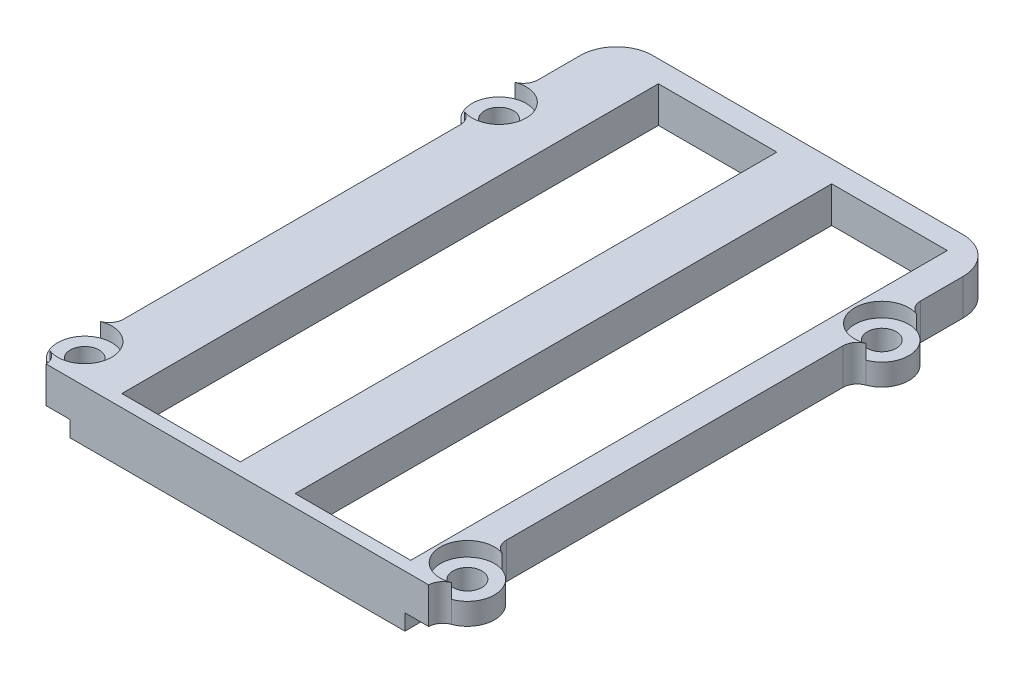
SolidWorks part; units mm, degrees
ref_plane "Front Plane" through (0, 0, 0) normal (0, 0, 1) x (1, 0, 0)
ref_plane "Top Plane" through (0, 0, 0) normal (0, 1, 0) x (1, 0, 0)
ref_plane "Right Plane" through (0, 0, 0) normal (1, 0, 0) x (0, 0, -1)
sketch "Sketch2" plane through (0, 0, 0) normal (0, 1, 0) x (1, 0, 0)
  line L0 (57.16, 49.7639) -> (4.16, 49.7639)
  line L1 (4.16, 49.7639) -> (4.16, 38.8921)
  line L2 (4.16, 28.1101) -> (4.16, -18.4867)
  line L4 (4.16, -29.2361) -> (7.16, -29.2361)
  line L8 (54.16, -29.2361) -> (57.16, -29.2361)
  line L10 (57.16, -18.4867) -> (57.16, 28.1101)
  line L12 (7.16, -29.2361) -> (54.16, -29.2361)
  line L23 (57.16, 38.8921) -> (57.16, 49.7639)
  circle A0 centre (4.16, 33.5011) radius 2
  circle A1 centre (57.16, 33.5011) radius 2
  circle A2 centre (57.16, -23.8776) radius 2
  circle A3 centre (4.16, -23.8776) radius 2
  arc A18 (2.8557, 37.0169) -> (4.16, 38.8921) centre (2.16, 38.8921) ccw
  arc A19 (2.8557, 37.0169) -> (2.8557, 29.9852) centre (4.16, 33.5011) ccw
  arc A20 (4.16, 28.1101) -> (2.8557, 29.9852) centre (2.16, 28.1101) ccw
  arc A21 (2.8557, -20.3618) -> (4.16, -18.4867) centre (2.16, -18.4867) ccw
  arc A22 (2.8557, -20.3618) -> (2.8558, -27.3935) centre (4.16, -23.8776) ccw
  arc A23 (4.16, -29.2361) -> (2.8558, -27.3935) centre (2.1603, -29.2687) ccw
  arc A24 (58.4642, -27.3935) -> (57.16, -29.2361) centre (59.1597, -29.2687) ccw
  arc A25 (58.4642, -27.3935) -> (58.4643, -20.3618) centre (57.16, -23.8776) ccw
  arc A26 (57.16, -18.4867) -> (58.4643, -20.3618) centre (59.16, -18.4867) ccw
  arc A27 (58.4643, 29.9852) -> (57.16, 28.1101) centre (59.16, 28.1101) ccw
  arc A28 (58.4643, 29.9852) -> (58.4643, 37.0169) centre (57.16, 33.5011) ccw
  arc A29 (57.16, 38.8921) -> (58.4643, 37.0169) centre (59.16, 38.8921) ccw
extrude "Boss-Extrude1" add sketch "Sketch2" along normal blind 3
sketch "Sketch3" plane through (0, 3, 0) normal (0, 1, 0) x (1, 0, 0)
  line L8 (57.16, 38.8921) -> (57.16, 49.7639)
  line L11 (57.16, 49.7639) -> (4.16, 49.7639)
  line L15 (4.16, 49.7639) -> (4.16, 38.8921)
  line L24 (4.16, 28.1101) -> (4.16, -18.4867)
  line L26 (4.16, -29.2361) -> (57.16, -29.2361)
  line L33 (57.16, -18.4867) -> (57.16, 28.1101)
  line L34 (57.16, 38.8921) -> (57.16, 49.7639)
  line L35 (57.16, 49.7639) -> (4.16, 49.7639)
  line L36 (4.16, 49.7639) -> (4.16, 38.8921)
  line L37 (4.16, 28.1101) -> (4.16, -18.4867)
  line L38 (4.16, -29.2361) -> (57.16, -29.2361)
  line L39 (57.16, -18.4867) -> (57.16, 28.1101)
  arc A7 (2.8557, 29.9852) -> (2.8557, 37.0169) centre (4.16, 33.5011) ccw
  arc A8 (58.4643, 37.0169) -> (58.4643, 29.9852) centre (57.16, 33.5011) ccw
  arc A9 (58.4643, -20.3618) -> (58.4642, -27.3935) centre (57.16, -23.8776) ccw
  arc A10 (2.8558, -27.3935) -> (2.8557, -20.3618) centre (4.16, -23.8776) ccw
  arc A48 (2.8557, 37.0169) -> (4.16, 38.8921) centre (2.16, 38.8921) ccw
  arc A53 (2.8557, 37.0169) -> (2.8557, 29.9852) centre (4.16, 33.5011) ccw
  arc A56 (4.16, 28.1101) -> (2.8557, 29.9852) centre (2.16, 28.1101) ccw
  arc A59 (2.8557, -20.3618) -> (4.16, -18.4867) centre (2.16, -18.4867) ccw
  arc A62 (2.8557, -20.3618) -> (2.8558, -27.3935) centre (4.16, -23.8776) ccw
  arc A76 (4.16, -29.2361) -> (2.8558, -27.3935) centre (2.1603, -29.2687) ccw
  arc A77 (58.4642, -27.3935) -> (57.16, -29.2361) centre (59.1597, -29.2687) ccw
  arc A78 (58.4642, -27.3935) -> (58.4643, -20.3618) centre (57.16, -23.8776) ccw
  arc A79 (57.16, -18.4867) -> (58.4643, -20.3618) centre (59.16, -18.4867) ccw
  arc A80 (58.4643, 29.9852) -> (57.16, 28.1101) centre (59.16, 28.1101) ccw
  arc A81 (58.4643, 29.9852) -> (58.4643, 37.0169) centre (57.16, 33.5011) ccw
  arc A82 (57.16, 38.8921) -> (58.4643, 37.0169) centre (59.16, 38.8921) ccw
  arc A83 (2.8557, 37.0169) -> (4.16, 38.8921) centre (2.16, 38.8921) ccw
  arc A85 (4.16, 28.1101) -> (2.8557, 29.9852) centre (2.16, 28.1101) ccw
  arc A86 (2.8557, -20.3618) -> (4.16, -18.4867) centre (2.16, -18.4867) ccw
  arc A88 (4.16, -29.2361) -> (2.8558, -27.3935) centre (2.1603, -29.2687) ccw
  arc A89 (58.4642, -27.3935) -> (57.16, -29.2361) centre (59.1597, -29.2687) ccw
  arc A91 (57.16, -18.4867) -> (58.4643, -20.3618) centre (59.16, -18.4867) ccw
  arc A92 (58.4643, 29.9852) -> (57.16, 28.1101) centre (59.16, 28.1101) ccw
  arc A94 (57.16, 38.8921) -> (58.4643, 37.0169) centre (59.16, 38.8921) ccw
  dimension "D1" = 0
extrude "Boss-Extrude2" add sketch "Sketch3" along normal blind 2
fillet "Fillet1" radius 5 2 edges at (4.16, 2.5, -49.7639) (57.16, 2.5, -49.7639)
sketch "Sketch4" plane through (0, 5, 0) normal (0, 1, 0) x (1, 0, 0)
  line L2 (52.96, -27.5361) -> (52.96, 46.7639)
  line L3 (36.96, -27.5361) -> (52.96, -27.5361)
  line L5 (12.96, -27.5361) -> (29.36, -27.5361)
  line L9 (36.96, 46.7639) -> (52.96, 46.7639)
  line L10 (12.96, 46.7639) -> (29.36, 46.7639)
  line L20 (12.96, 46.7639) -> (12.96, -27.5361)
  line L21 (29.36, 46.7639) -> (29.36, -27.5361)
  line L22 (36.96, 46.7639) -> (36.96, -27.5361)
extrude "Cut-Extrude1" cut sketch "Sketch4" against normal blind 10
sketch "Sketch7" plane through (0, 0, 0) normal (0, -1, 0) x (1, 0, 0)
  line L13 (53.86, 29.2361) -> (53.86, -43.8057)
  line L14 (7.46, -43.8057) -> (7.46, 29.2361)
  line L15 (52.96, 27.5361) -> (52.96, -43.8057)
  line L16 (8.46, -43.8057) -> (8.46, 27.5361)
  line L17 (7.46, -43.8057) -> (8.46, -43.8057)
  line L18 (8.46, -47.2639) -> (8.46, 29.2361) construction
  line L19 (7.46, -47.2639) -> (7.46, 29.2361) construction
  line L20 (52.96, -43.8057) -> (53.86, -43.8057)
  line L21 (7.46, 29.2361) -> (53.86, 29.2361)
  line L23 (8.46, 27.5361) -> (52.96, 27.5361)
  dimension "D1" = 1
extrude "Boss-Extrude3" add sketch "Sketch7" along normal blind 2.2
